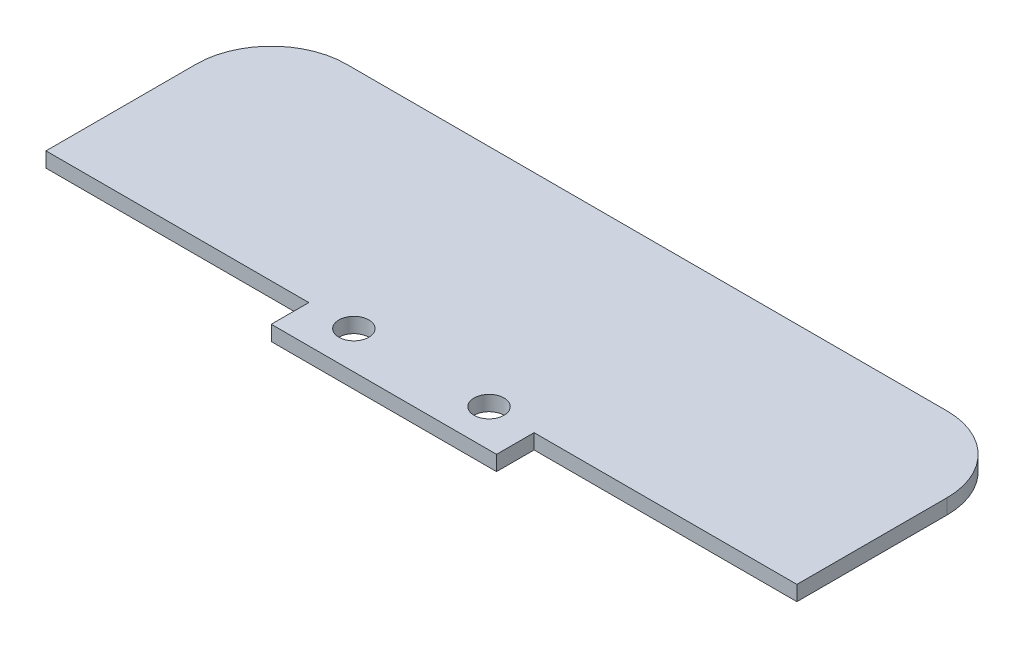
SolidWorks part; units mm, degrees
ref_plane "Front Plane" through (0, 0, 0) normal (0, 0, 1) x (1, 0, 0)
ref_plane "Top Plane" through (0, 0, 0) normal (0, 1, 0) x (1, 0, 0)
ref_plane "Right Plane" through (0, 0, 0) normal (1, 0, 0) x (0, 0, -1)
sketch "Sketch1" plane through (0, 0, 0) normal (0, 1, 0) x (1, 0, 0)
  line L0 (0, 0) -> (0, 10.5) construction
  line L2 (50, 15) -> (50, -15)
  line L3 (50, -15) -> (15, -15)
  line L4 (-50, 15) -> (-50, -15)
  line L5 (50, 15) -> (-50, -15) construction
  line L6 (50, -15) -> (-50, 15) construction
  line L7 (-15, -15) -> (-15, -20)
  line L8 (-15, -20) -> (15, -20)
  line L9 (15, -20) -> (15, -15)
  line L10 (-15, -15) -> (-50, -15)
  line L11 (-50, 15) -> (50, 15)
  circle A0 centre (-9, -15) radius 2
  circle A1 centre (9, -15) radius 2
  point P0 (0, 0)
  dimension "D6" = 6
  dimension "D1" = 100
  dimension "D2" = 30
  dimension "D3" = 35
  dimension "D4" = 30
  dimension "D5" = 5
  dimension "D7" = 6
  dimension "D8" = 5
  dimension "D9" = 5
  dimension "D10" = 0
  dimension "D12" = 30
extrude "Boss-Extrude1" add sketch "Sketch1" along normal blind 2
fillet "Fillet1" radius 10 2 edges at (50, 1, -15) (-50, 1, -15)
